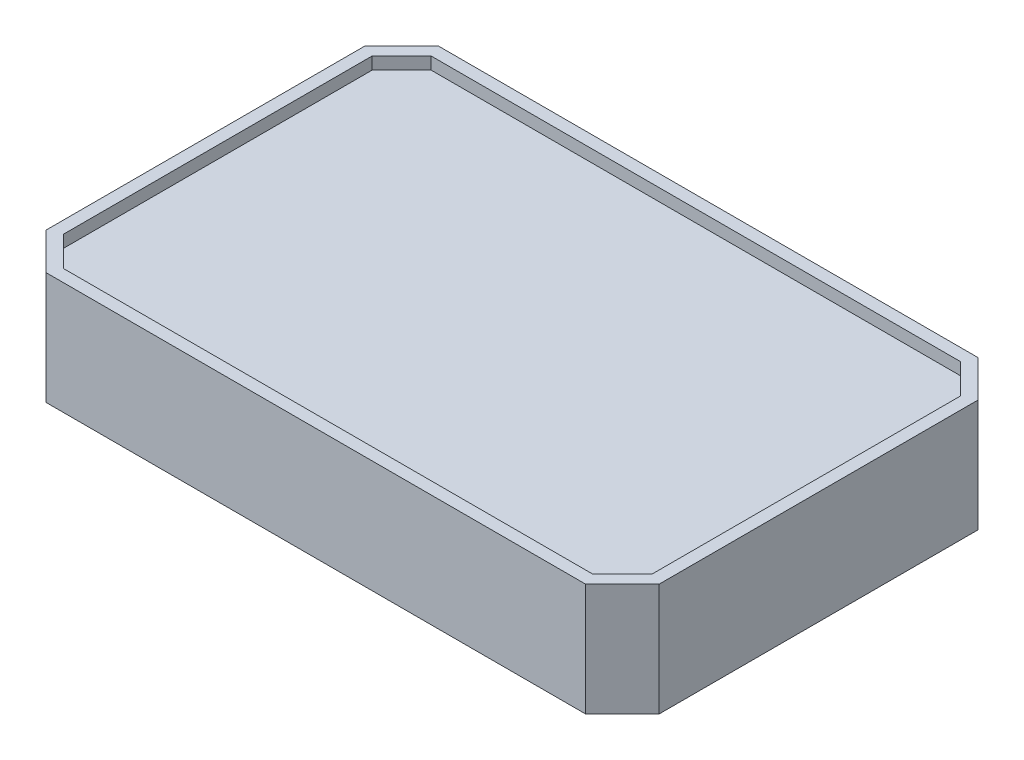
SolidWorks part; units mm, degrees
ref_plane "Plano frontal" through (0, 0, 0) normal (0, 0, 1) x (1, 0, 0)
ref_plane "Plano superior" through (0, 0, 0) normal (0, 1, 0) x (1, 0, 0)
ref_plane "Plano direito" through (0, 0, 0) normal (1, 0, 0) x (0, 0, -1)
sketch "Esboço1" plane through (0, 0, 0) normal (0, 1, 0) x (1, 0, 0)
  line L0 (2.5, 1.6) -> (-2.5, -1.6) construction
  line L1 (-2.5, 1.6) -> (2.5, 1.6)
  line L2 (-2.5, 1.6) -> (-2.5, -1.6)
  line L3 (-2.5, -1.6) -> (2.5, -1.6)
  line L4 (2.5, 1.6) -> (2.5, -1.6)
  dimension "D1" = 5
  dimension "D2" = 3.2
extrude "Extrusão1" add sketch "Esboço1" along normal blind 0.917
chamfer "Chanfro3" distance 0.3 angle 45 1 edges at (2.5, 0.4585, 1.6)
chamfer "Chanfro4" distance 0.3 angle 45 1 edges at (-2.5, 0.4585, 1.6)
chamfer "Chanfro5" distance 0.3 angle 45 1 edges at (2.5, 0.4585, -1.6)
chamfer "Chanfro6" distance 0.3 angle 45 1 edges at (-2.5, 0.4585, -1.6)
sketch "Esboço4" plane through (0, 0, 0) normal (0, 1, 0) x (1, 0, 0)
  line L0 (1.25, 0.75) -> (1.25, 1.55)
  line L1 (1.25, 1.55) -> (2.1793, 1.55)
  line L2 (2.1793, 1.55) -> (2.45, 1.2793)
  line L3 (2.45, 1.2793) -> (2.45, 0.75)
  line L4 (2.45, 0.75) -> (1.25, 0.75)
  line L6 (2.2, 1.6) -> (-2.2, 1.6) construction
  line L7 (2.5, -1.3) -> (2.5, 1.3) construction
  line L10 (2.2, 1.6) -> (2.5, 1.3) construction
  dimension "D1" = 1.2
  dimension "D2" = 0.8
  dimension "D3" = 0.05
  dimension "D4" = 0.05
  dimension "D5" = 0.05
extrude "Extrusão6" cut sketch "Esboço4" along normal blind 0.1
sketch "Esboço6" plane through (0, 0, 0) normal (0, 1, 0) x (1, 0, 0)
  line L0 (1.25, -1.55) -> (1.25, -0.75)
  line L1 (1.25, -0.75) -> (2.45, -0.75)
  line L2 (2.45, -0.75) -> (2.45, -1.2793)
  line L3 (2.45, -1.2793) -> (2.1793, -1.55)
  line L4 (2.1793, -1.55) -> (1.25, -1.55)
  line L6 (-2.2, -1.6) -> (2.2, -1.6) construction
  line L8 (2.5, -1.3) -> (2.5, 1.3) construction
  line L9 (2.5, -1.3) -> (2.2, -1.6) construction
  dimension "D1" = 1.2
  dimension "D2" = 0.8
  dimension "D3" = 0.05
  dimension "D4" = 0.05
  dimension "D5" = 0.05
extrude "Extrusão8" cut sketch "Esboço6" along normal blind 0.1
sketch "Esboço7" plane through (0, 0, 0) normal (0, 1, 0) x (1, 0, 0)
  line L0 (-2.45, -0.75) -> (-1.5187, -0.75)
  line L1 (-1.5187, -0.75) -> (-1.25, -1.0187)
  line L2 (-1.25, -1.0187) -> (-1.25, -1.55)
  line L3 (-1.25, -1.55) -> (-2.1793, -1.55)
  line L4 (-2.1793, -1.55) -> (-2.45, -1.2793)
  line L5 (-2.45, -1.2793) -> (-2.45, -0.75)
  line L6 (-2.2, -1.6) -> (2.2, -1.6) construction
  line L7 (-2.5, 1.3) -> (-2.5, -1.3) construction
  line L8 (-2.2, -1.6) -> (-2.5, -1.3) construction
  dimension "D1" = 0.05
  dimension "D2" = 0.05
  dimension "D3" = 0.05
  dimension "D4" = 1.2
  dimension "D5" = 0.8
  dimension "D6" = 0.38
extrude "Extrusão9" cut sketch "Esboço7" along normal blind 0.1
sketch "Esboço10" plane through (0, 0.917, 0) normal (0, 1, 0) x (1, 0, 0)
  line L0 (-2.4, 1.2586) -> (-2.1586, 1.5)
  line L1 (-2.1586, 1.5) -> (2.1586, 1.5)
  line L2 (2.1586, 1.5) -> (2.4, 1.2586)
  line L3 (2.4, 1.2586) -> (2.4, -1.2586)
  line L4 (2.4, -1.2586) -> (2.1586, -1.5)
  line L5 (2.1586, -1.5) -> (-2.1586, -1.5)
  line L6 (-2.1586, -1.5) -> (-2.4, -1.2586)
  line L7 (-2.4, -1.2586) -> (-2.4, 1.2586)
  line L8 (-2.2, -1.6) -> (2.2, -1.6) construction
  line L9 (2.2, 1.6) -> (-2.2, 1.6) construction
  line L10 (-2.5, 1.3) -> (-2.5, -1.3) construction
  line L11 (2.5, -1.3) -> (2.5, 1.3) construction
  line L12 (-2.2, 1.6) -> (-2.5, 1.3) construction
  line L13 (2.5, 1.3) -> (2.2, 1.6) construction
  line L14 (2.2, -1.6) -> (2.5, -1.3) construction
  line L15 (-2.5, -1.3) -> (-2.2, -1.6) construction
  dimension "D1" = 0.1
  dimension "D2" = 0.1
  dimension "D3" = 0.1
  dimension "D4" = 0.1
  dimension "D5" = 0.1
  dimension "D6" = 0.1
  dimension "D7" = 0.1
  dimension "D8" = 0.1
extrude "Extrusão13" cut sketch "Esboço10" against normal blind 0.1
sketch "Esboço11" plane through (0, 0, 0) normal (0, 1, 0) x (1, 0, 0)
  line L0 (-2.45, 1.2793) -> (-2.45, 0.75)
  line L1 (-2.45, 0.75) -> (-1.25, 0.75)
  line L2 (-1.25, 0.75) -> (-1.25, 1.55)
  line L3 (-1.25, 1.55) -> (-2.1793, 1.55)
  line L4 (-2.1793, 1.55) -> (-2.45, 1.2793)
  line L5 (-2.5, 1.3) -> (-2.2, 1.6) construction
  line L6 (2.2, 1.6) -> (-2.2, 1.6) construction
  line L7 (-2.5, 1.3) -> (-2.5, -1.3) construction
  dimension "D1" = 1.2
  dimension "D2" = 0.8
  dimension "D3" = 0.05
  dimension "D4" = 0.05
  dimension "D5" = 0.05
extrude "Extrusão14" cut sketch "Esboço11" along normal blind 0.1
